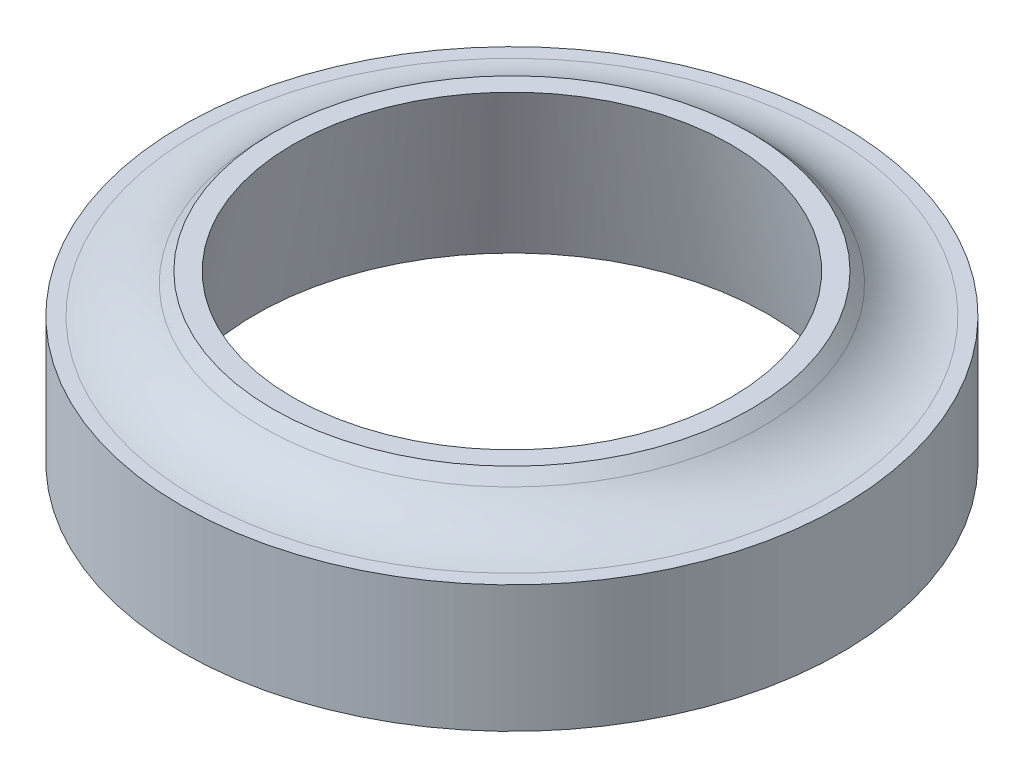
SolidWorks part; units mm, degrees
ref_plane "Alzado" through (0, 0, 0) normal (0, 0, 1) x (1, 0, 0)
ref_plane "Planta" through (0, 0, 0) normal (0, 1, 0) x (1, 0, 0)
ref_plane "Vista lateral" through (0, 0, 0) normal (1, 0, 0) x (0, 0, -1)
sketch "Croquis1" plane through (0, 0, 0) normal (0, 0, 1) x (1, 0, 0)
  line L0 (0, 13.0591) -> (0, -7.6406) construction
  line L6 (-7, 0.0149) -> (-5.9814, 4.539)
  line L7 (-5.9814, 4.539) -> (-6.5289, 4.539)
  line L8 (-6.5289, 4.539) -> (-7.548, 3.4798)
  line L9 (-7.548, 3.4798) -> (-9, 3.4798)
  line L10 (-9, 3.4798) -> (-9, 0.0149)
  line L11 (-9, 0.0149) -> (-7, 0.0149)
  line L12 (8.8, 0.0149) -> (-8.8, 0.0149) construction
  point P5 (-4.8658, 4.3742)
  point P10 (-4.7771, 4.6561)
  point P11 (-5.6262, 4.6324)
  point P12 (-5.8096, 4.7109)
  point P13 (-6.0029, 4.6894)
  point P14 (-5.8311, 4.6035)
  point P15 (-5.9814, 4.539)
  dimension "D1" = 9
  dimension "D2" = 7
revolve "Revolución1" add sketch "Croquis1" angle 360 about L0
fillet "Redondeo1" radius 2.5 1 edges at (0, 3.4798, 7.548)
